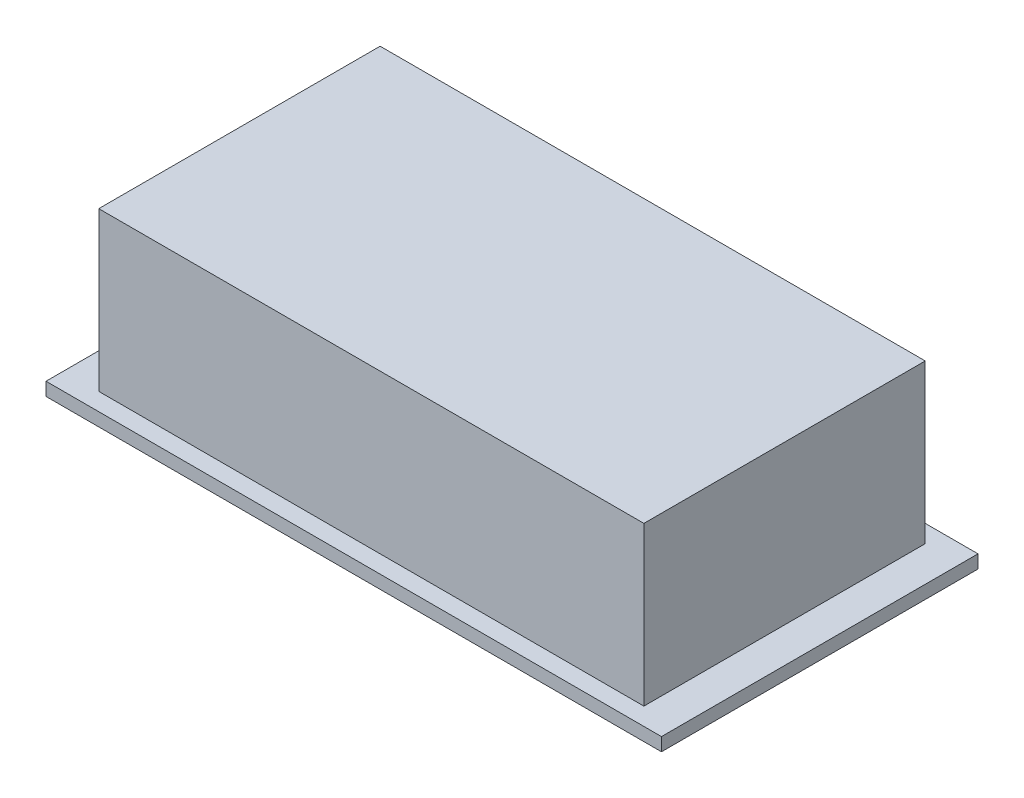
SolidWorks part; units mm, degrees
ref_plane "Front Plane" through (0, 0, 0) normal (0, 0, 1) x (1, 0, 0)
ref_plane "Top Plane" through (0, 0, 0) normal (0, 1, 0) x (1, 0, 0)
ref_plane "Right Plane" through (0, 0, 0) normal (1, 0, 0) x (0, 0, -1)
sketch "Sketch1" plane through (0, 0, 0) normal (0, 1, 0) x (1, 0, 0)
  line L1 (-35, -18) -> (35, -18)
  line L2 (-35, -18) -> (-35, 18)
  line L3 (-35, 18) -> (35, 18)
  line L4 (35, -18) -> (35, 18)
  line L5 (-35, -18) -> (35, 18) construction
  line L6 (-35, 18) -> (35, -18) construction
  point P0 (0, 0)
  dimension "D1" = 70
  dimension "D2" = 36
extrude "Boss-Extrude1" add sketch "Sketch1" along normal blind 1.5
sketch "Sketch2" plane through (0, 1.5, 0) normal (0, 1, 0) x (1, 0, 0)
  line L0 (35, 18) -> (-35, 18) construction
  line L1 (-31, -16) -> (31, -16)
  line L2 (-31, -16) -> (-31, 16)
  line L3 (-31, 16) -> (31, 16)
  line L4 (31, -16) -> (31, 16)
  line L5 (-31, -16) -> (31, 16) construction
  line L6 (-31, 16) -> (31, -16) construction
  line L7 (-35, 18) -> (-35, -18) construction
  point P0 (0, 0)
  dimension "D1" = 2
  dimension "D2" = 4
extrude "Boss-Extrude2" add sketch "Sketch2" along normal blind 18
